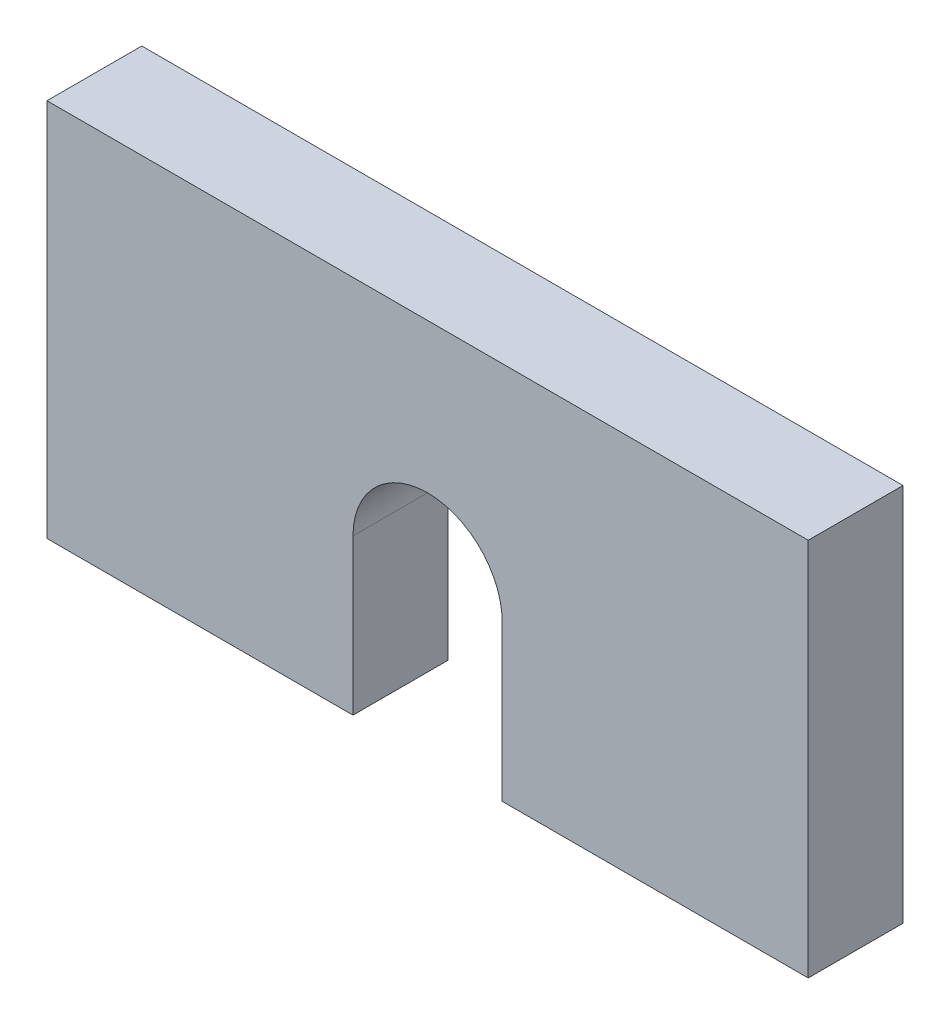
SolidWorks part; units mm, degrees
material "Plain Carbon Steel"
ref_plane "Front Plane" through (0, 0, 0) normal (0, 0, 1) x (1, 0, 0)
ref_plane "Top Plane" through (0, 0, 0) normal (0, 1, 0) x (1, 0, 0)
ref_plane "Right Plane" through (0, 0, 0) normal (1, 0, 0) x (0, 0, -1)
sketch "Sketch1" plane through (0, 0, 0) normal (0, 0, 1) x (1, 0, 0)
  line L0 (-5, 0) -> (-5, -10.4)
  line L1 (-25.5, 15) -> (25.5, 15)
  line L2 (-25.5, 15) -> (-25.5, -10.4)
  line L3 (-25.5, -10.4) -> (-5, -10.4)
  line L4 (25.5, 15) -> (25.5, -10.4)
  line L5 (5, 0) -> (5, -10.4)
  line L6 (5, -10.4) -> (25.5, -10.4)
  arc A0 (5, 0) -> (-5, 0) centre (0, 0) ccw
  point P1 (0, 15)
  dimension "D1" = 10
  dimension "D2" = 51
  dimension "D3" = 15
  dimension "D4" = 10.4
extrude "Boss-Extrude1" add sketch "Sketch1" along normal blind 6.35
